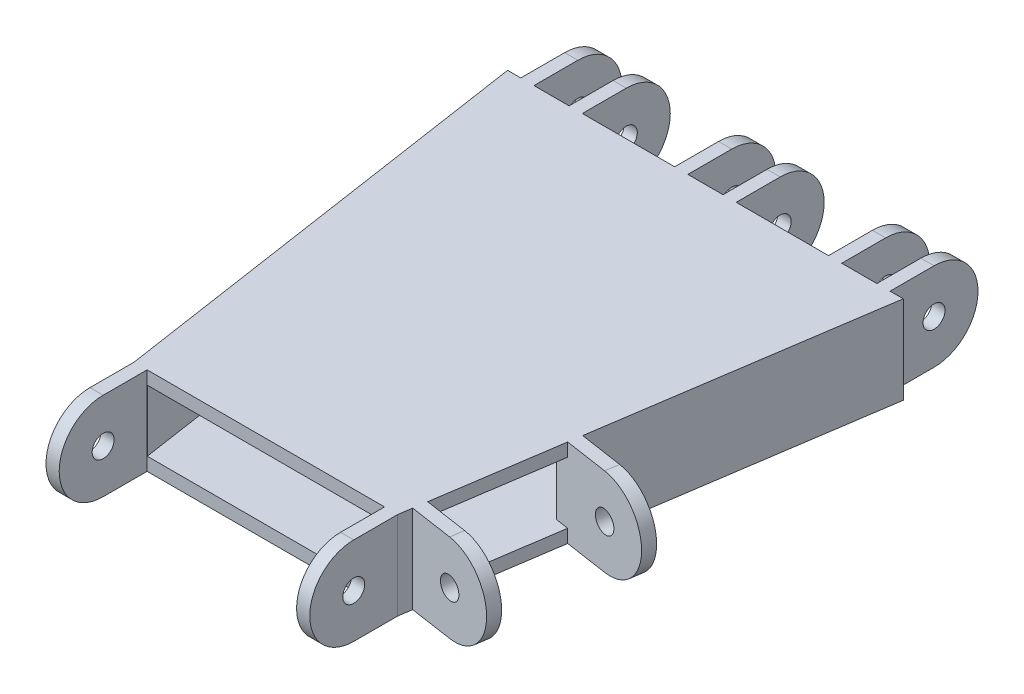
SolidWorks part; units mm, degrees
ref_plane "Front Plane" through (0, 0, 0) normal (0, 0, 1) x (1, 0, 0)
ref_plane "Top Plane" through (0, 0, 0) normal (0, 1, 0) x (1, 0, 0)
ref_plane "Right Plane" through (0, 0, 0) normal (1, 0, 0) x (0, 0, -1)
sketch "Sketch1" plane through (0, 0, 0) normal (0, 1, 0) x (1, 0, 0)
  line L0 (-45, 0) -> (45, 0)
  line L1 (45, 0) -> (30, -100)
  line L2 (30, -100) -> (-30, -100)
  line L3 (-30, -100) -> (-45, 0)
  point P2 (0, 0)
  dimension "D1" = 60
  dimension "D3" = 90
  dimension "D4" = 100
extrude "Boss-Extrude1" add sketch "Sketch1" along normal mid plane 20
sketch "Sketch2" plane through (0, 0, 0) normal (1, 0, 0) x (0, 0, -1)
  line L0 (0, 10) -> (0, -10) construction
  line L1 (0, -10) -> (-100, -10) construction
  line L2 (0, 10) -> (0, -10) construction
  line L3 (0, -10) -> (-100, -10) construction
  line L5 (0, 10) -> (10, 10)
  line L6 (0, 10) -> (0, -10)
  line L7 (0, -10) -> (10, -10)
  arc A0 (10, -10) -> (10, 10) centre (10, 0) ccw
  circle A1 centre (10, 0) radius 2.5
  dimension "D2" = 10
  dimension "D3" = 5
  dimension "D1" = 10
extrude "Boss-Extrude2" add sketch "Sketch2" along normal mid plane 14 from offset 35
pattern_linear "LPattern1" count 3 spacing 35 along (-1, 0, 0) of "Boss-Extrude2"
shell "Shell1" thickness 3
sketch "Sketch3" plane through (0, 0, 0) normal (0, 0, 1) x (1, 0, 0)
  line L0 (-42, 10) -> (-42, -10) construction
  line L1 (-42, -10) -> (-45, -10) construction
  line L2 (-45, -10) -> (-45, 10) construction
  line L3 (-45, 10) -> (-42, 10) construction
  line L4 (42, -10) -> (42, 10) construction
  line L5 (42, 10) -> (45, 10) construction
  line L6 (45, 10) -> (45, -10) construction
  line L7 (45, -10) -> (42, -10) construction
  line L8 (28, -10) -> (7, -10) construction
  line L9 (28, 10) -> (7, 10) construction
  line L10 (-7, 10) -> (-28, 10) construction
  line L11 (-7, -10) -> (-28, -10) construction
  line L12 (-45, 10) -> (-45, -10) construction
  line L13 (-42, 10) -> (-45, 10) construction
  line L14 (45, 10) -> (42, 10) construction
  line L15 (-42, 10) -> (-42, -10) construction
  line L16 (-42, -10) -> (-45, -10) construction
  line L17 (-45, -10) -> (-45, 10) construction
  line L18 (-45, 10) -> (-42, 10) construction
  line L19 (42, -10) -> (42, 10) construction
  line L20 (42, 10) -> (45, 10) construction
  line L21 (45, 10) -> (45, -10) construction
  line L22 (45, -10) -> (42, -10) construction
  line L23 (28, -10) -> (7, -10) construction
  line L24 (28, 10) -> (7, 10) construction
  line L25 (-7, 10) -> (-28, 10) construction
  line L26 (-7, -10) -> (-28, -10) construction
  line L27 (-45, 10) -> (-45, -10) construction
  line L28 (-42, 10) -> (-45, 10) construction
  line L29 (45, 10) -> (42, 10) construction
  line L31 (42, 10) -> (28, 10) construction
  line L32 (42, 10) -> (42, -10) construction
  line L33 (42, -10) -> (28, -10) construction
  line L34 (28, 10) -> (28, -10) construction
  line L35 (7, 10) -> (-7, 10) construction
  line L36 (7, 10) -> (7, -10) construction
  line L37 (7, -10) -> (-7, -10) construction
  line L38 (-7, 10) -> (-7, -10) construction
  line L39 (-28, 10) -> (-42, 10) construction
  line L40 (-28, 10) -> (-28, -10) construction
  line L41 (-28, -10) -> (-42, -10) construction
  line L42 (-42, 10) -> (-42, -10) construction
  line L43 (39, 10) -> (31, 10)
  line L44 (39, 10) -> (39, -10)
  line L45 (39, -10) -> (31, -10)
  line L46 (31, 10) -> (31, -10)
  line L47 (4, 10) -> (-4, 10)
  line L48 (4, 10) -> (4, -10)
  line L49 (4, -10) -> (-4, -10)
  line L50 (-4, 10) -> (-4, -10)
  line L51 (-31, 10) -> (-39, 10)
  line L52 (-31, 10) -> (-31, -10)
  line L53 (-31, -10) -> (-39, -10)
  line L54 (-39, 10) -> (-39, -10)
  dimension "D1" = 3
  dimension "D2" = 3
  dimension "D3" = 3
  dimension "D4" = 3
  dimension "D5" = 3
  dimension "D6" = 3
extrude "Cut-Extrude1" cut sketch "Sketch3" against normal blind 20
ref_plane "thumb plane" through (-14.0098, 0, 93.3985) normal (-0.1483, 0, 0.9889) x (0.9889, 0, 0.1483)
sketch "Sketch5" plane through (-14.0098, 0, 93.3985) normal (-0.1483, 0, 0.9889) x (0.9889, 0, 0.1483)
  line L0 (44.5021, 10) -> (44.5021, -10) construction
  line L1 (44.5021, 10) -> (44.5021, -10) construction
  line L3 (44.5021, 10) -> (54.5021, 10)
  line L4 (44.5021, 10) -> (44.5021, -10)
  line L5 (44.5021, -10) -> (54.5021, -10)
  arc A0 (54.5021, -10) -> (54.5021, 10) centre (54.5021, 0) ccw
  circle A1 centre (54.5021, 0) radius 2.5
  dimension "D2" = 5
  dimension "D1" = 10
extrude "Boss-Extrude3" add sketch "Sketch5" against normal blind 3 from offset 3 offset against normal yes
pattern_linear "LPattern2" count 2 spacing 31 along (0.1483, 0, -0.9889) of "Boss-Extrude3"
sketch "Sketch6" plane through (44.0098, 0, 6.6015) normal (0.9889, 0, 0.1483) x (0.1483, 0, -0.9889)
  line L0 (-88.4434, 10) -> (-88.4434, -10) construction
  line L1 (-88.4434, 7) -> (-60.4434, 7)
  line L2 (-88.4434, 7) -> (-88.4434, -7)
  line L3 (-88.4434, -7) -> (-60.4434, -7)
  line L4 (-60.4434, 7) -> (-60.4434, -7)
  line L5 (-60.4434, 10) -> (-60.4434, -10) construction
  line L6 (-88.4434, 10) -> (-60.4434, 10) construction
  line L7 (-88.4434, -10) -> (-60.4434, -10) construction
  dimension "D1" = 3
  dimension "D2" = 3
extrude "Cut-Extrude2" cut sketch "Sketch6" against normal blind 3
sketch "Sketch7" plane through (0, 0, 0) normal (1, 0, 0) x (0, 0, -1)
  line L0 (-100, 10) -> (-100, -10) construction
  line L1 (-100, 10) -> (-100, -10) construction
  line L3 (-100, 10) -> (-110, 10)
  line L4 (-100, 10) -> (-100, -10)
  line L5 (-100, -10) -> (-110, -10)
  arc A0 (-110, 10) -> (-110, -10) centre (-110, 0) ccw
  circle A1 centre (-110, 0) radius 2.5
  dimension "D1" = 10
  dimension "D3" = 5
  dimension "D2" = 10
extrude "Boss-Extrude4" add sketch "Sketch7" against normal blind 3 from offset 30
pattern_linear "LPattern3" count 2 spacing 57 along (-1, 0, 0) of "Boss-Extrude4"
